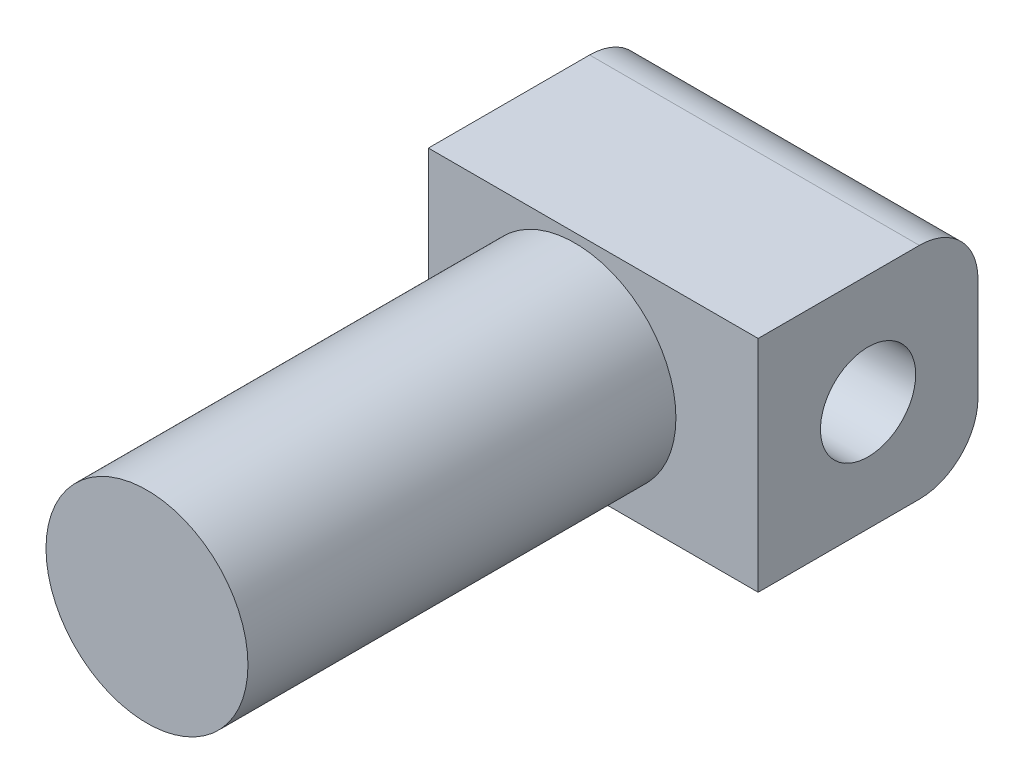
SolidWorks part; units mm, degrees
material "6061-T6 (SS)"
ref_plane "Front Plane" through (0, 0, 0) normal (1, 0, 0) x (0, 1, 0)
ref_plane "Top Plane" through (0, 0, 0) normal (0, 0, 1) x (0, 1, 0)
ref_plane "Right Plane" through (0, 0, 0) normal (0, 1, 0) x (-1, 0, 0)
sketch "Sketch1" plane through (0, 0, 0) normal (0, 0, 1) x (0, 1, 0)
  line L1 (0, 0) -> (-7.62, 0)
  line L2 (0, 0) -> (0, 11.43)
  line L3 (0, 11.43) -> (-7.62, 11.43)
  line L4 (-7.62, 0) -> (-7.62, 11.43)
  dimension "D1" = 7.62
  dimension "D2" = 11.43
extrude "Boss-Extrude1" add sketch "Sketch1" along normal blind 7.62
sketch "Sketch2" plane through (0, 0, 7.62) normal (0, 0, 1) x (1, 0, 0)
  line L0 (-11.43, -3.81) -> (0, -3.81) construction
  line L1 (-11.43, 0) -> (-11.43, -7.62) construction
  line L2 (0, -7.62) -> (0, 0) construction
  circle A0 centre (-6.35, -3.81) radius 3.5
  point P6 (-6.35, -3.81)
  dimension "D2" = 7
  dimension "D1" = 5.08
extrude "Boss-Extrude2" add sketch "Sketch2" along normal blind 14.8336
sketch "Sketch3" plane through (0, 0, 0) normal (1, 0, 0) x (0, 1, 0)
  line L0 (-7.62, 7.62) -> (0, 0) construction
  line L1 (0, 7.62) -> (-7.62, 0) construction
hole_wizard "Tap Drill for M4x0.7 Tap1" positions "Sketch4" profile "Sketch5" hole size "M4x0.7" standard "ANSI Metric" end condition through all
sketch "Sketch4" plane through (0, 0, 0) normal (1, 0, 0) x (0, 0, -1)
  line L0 (-7.62, -7.62) -> (0, 0) construction
  point P0 (-3.81, -3.81)
sketch "Sketch5" plane through (0, -3.81, 3.81) normal (0, 1, 0) x (0, 0, -1)
  line L0 (0, 0) -> (0, 11.43)
  line L1 (0, 11.43) -> (1.65, 11.43)
  line L2 (1.65, 11.43) -> (1.65, 0)
  line L5 (1.65, 0) -> (0, 0)
  line L11 (0, -6.35) -> (0, 107.95) construction
  dimension "Thru Hole Dia." = 3.3
  dimension "Thru Hole Depth" = 11.43
fillet "Fillet1" radius 2.032 2 edges at (-5.715, 0, 0) (-5.715, -7.62, 0)
equation "\"D2@Sketch2\"=7mm"
